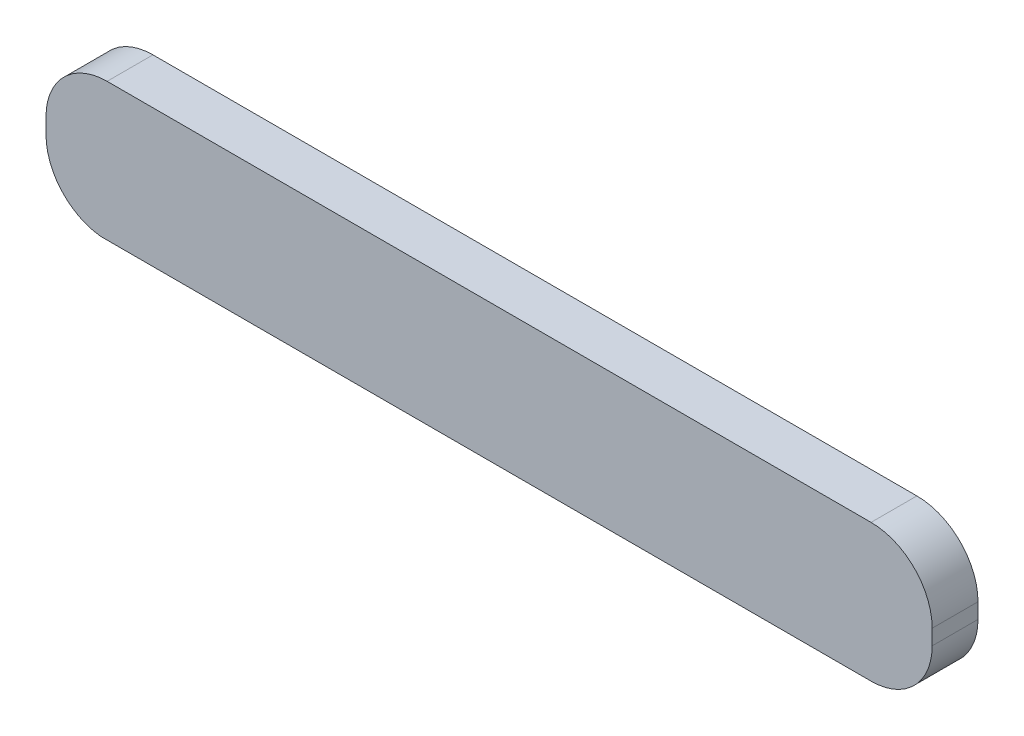
SolidWorks part; units mm, degrees
ref_plane "Plano frontal" through (0, 0, 0) normal (0, 0, 1) x (1, 0, 0)
ref_plane "Plano superior" through (0, 0, 0) normal (0, 1, 0) x (1, 0, 0)
ref_plane "Plano direito" through (0, 0, 0) normal (1, 0, 0) x (0, 0, -1)
sketch "Esboço1" plane through (0, 0, 0) normal (0, 0, 1) x (1, 0, 0)
  line L0 (-25, 22.5) -> (225, 22.5)
  line L1 (175, 31.4349) -> (175.8842, 31.4349)
  line L2 (245, 2.5) -> (245, -2.5)
  line L3 (225, -22.5) -> (-27.1405, -22.5)
  line L5 (-45, -2.6149) -> (-45, 2.5)
  line L6 (47.7568, -48.5365) -> (297.7568, -48.5365)
  line L7 (247.7568, -39.6016) -> (248.641, -39.6016)
  line L8 (297.7568, -93.5365) -> (45.6163, -93.5365)
  line L9 (27.7568, -73.6514) -> (27.7568, -68.5365)
  circle A0 centre (0, 0) radius 12.5
  circle A1 centre (0, 0) radius 4
  circle A2 centre (100, 0) radius 12.5
  circle A3 centre (100, 0) radius 4
  arc A4 (-45, -2.6149) -> (-27.1405, -22.5) centre (-25, -2.6149) ccw
  arc A5 (-45, 2.5) -> (-25, 22.5) centre (-25, 2.5) cw
  arc A6 (245, -2.5) -> (225, -22.5) centre (225, -2.5) cw
  arc A7 (225, 22.5) -> (245, 2.5) centre (225, 2.5) cw
  circle A8 centre (200, 0) radius 12.5
  circle A9 centre (200, 0) radius 4
  circle A10 centre (72.7568, -71.0365) radius 12.5
  circle A11 centre (72.7568, -71.0365) radius 4
  circle A12 centre (172.7568, -71.0365) radius 12.5
  circle A13 centre (172.7568, -71.0365) radius 4
  arc A14 (27.7568, -73.6514) -> (45.6163, -93.5365) centre (47.7568, -73.6514) ccw
  arc A15 (27.7568, -68.5365) -> (47.7568, -48.5365) centre (47.7568, -68.5365) cw
  arc A16 (317.7568, -73.5365) -> (297.7568, -93.5365) centre (297.7568, -73.5365) cw
  arc A17 (297.7568, -48.5365) -> (317.7568, -68.5365) centre (297.7568, -68.5365) cw
  circle A18 centre (272.7568, -71.0365) radius 12.5
  circle A19 centre (272.7568, -71.0365) radius 4
  point P7 (-25.2699, -22.5)
  point P23 (-29.1497, 22.2961)
  dimension "D1" = 25
  dimension "D2" = 8
  dimension "D3" = 25
  dimension "D4" = 8
  dimension "D7" = 20
  dimension "D8" = 20
  dimension "D5" = 22.5
  dimension "D9" = 22.5
  dimension "D10" = 100
  dimension "D11" = 100
  dimension "D13" = 22.5
  dimension "D14" = 45
  dimension "D15" = 45
  dimension "D16" = 25
  dimension "D17" = 8
  dimension "D18" = 25
  dimension "D19" = 8
  dimension "D21" = 20
  dimension "D22" = 20
  dimension "D6" = 45
  dimension "D12" = 250
  dimension "D20" = 45
  dimension "D23" = 22.5
  dimension "D24" = 22.5
  dimension "D25" = 250
  dimension "D26" = 100
  dimension "D27" = 100
  dimension "D28" = 22.5
  dimension "D29" = 45
  dimension "D30" = 45
extrude "Ressalto-extrusão1" add sketch "Esboço1" along normal blind 15 contours L3 A4 L5 A5 L0 A7 L2 A6
